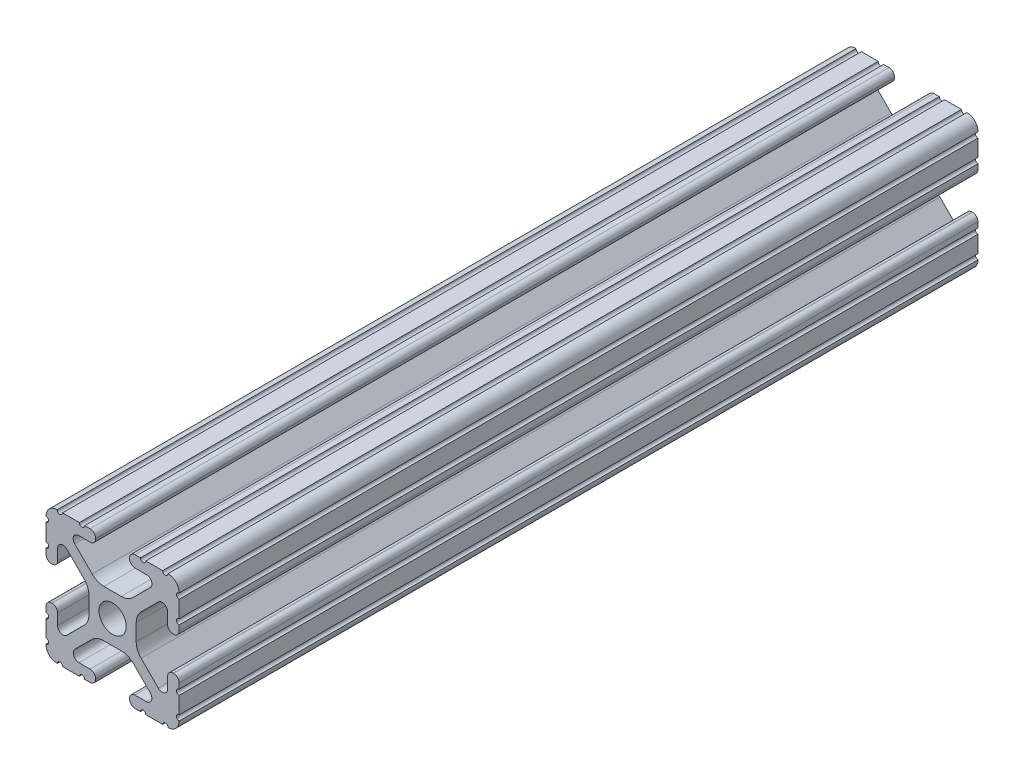
SolidWorks part; units mm, degrees
ref_plane "Front Plane" through (0, 0, 0) normal (0, 0, 1) x (1, 0, 0)
ref_plane "Top Plane" through (0, 0, 0) normal (0, 1, 0) x (1, 0, 0)
ref_plane "Right Plane" through (0, 0, 0) normal (1, 0, 0) x (0, 0, -1)
sketch "Sketch1" plane through (0, 0, 0) normal (0, 0, 1) x (1, 0, 0)
  line L0 (-7.207, 8.7244) -> (-3.8983, 5.4232)
  line L1 (-4.2875, 10.4902) -> (-6.4768, 10.4902)
  line L2 (-3.2385, 11.651) -> (-3.2385, 11.5392)
  line L3 (-5.3171, 12.7) -> (-4.2875, 12.7)
  line L4 (0, 13.4005) -> (0, -14.8534) construction
  line L5 (12.7, 0) -> (-13.9989, 0) construction
  line L6 (-9.5504, 12.7) -> (-6.3331, 12.7)
  line L7 (-12.7, 6.3331) -> (-12.7, 9.5504)
  line L8 (-12.7, 4.2875) -> (-12.7, 5.3171)
  line L9 (-11.5392, 3.2385) -> (-11.651, 3.2385)
  line L10 (-10.4902, 6.4021) -> (-10.4902, 4.2875)
  line L11 (-5.441, 3.8408) -> (-8.7371, 7.1294)
  line L12 (-4.5085, -1.5932) -> (-4.5085, 1.5932)
  line L13 (-1.7093, -4.4958) -> (1.7093, -4.4958)
  line L14 (3.9523, -5.4237) -> (7.1797, -8.6452)
  line L15 (6.4164, -10.4902) -> (4.2875, -10.4902)
  line L16 (3.2385, -11.5392) -> (3.2385, -11.651)
  line L17 (4.2875, -12.7) -> (5.3171, -12.7)
  line L18 (6.3331, -12.7) -> (9.5504, -12.7)
  line L19 (12.7, -9.5504) -> (12.7, -6.3331)
  line L20 (12.7, -5.3171) -> (12.7, -4.2875)
  line L21 (11.651, -3.2385) -> (11.5392, -3.2385)
  line L22 (10.4902, -4.2875) -> (10.4902, -6.4021)
  line L23 (8.7371, -7.1294) -> (5.441, -3.8408)
  line L24 (4.5085, -1.5932) -> (4.5085, 1.5932)
  line L25 (5.441, 3.8408) -> (8.7371, 7.1294)
  line L26 (10.4902, 6.4021) -> (10.4902, 4.2875)
  line L27 (11.5392, 3.2385) -> (11.651, 3.2385)
  line L28 (12.7, 4.2875) -> (12.7, 5.3171)
  line L29 (12.7, 6.3331) -> (12.7, 9.5504)
  line L30 (9.5504, 12.7) -> (6.3331, 12.7)
  line L31 (5.3171, 12.7) -> (4.2875, 12.7)
  line L32 (3.2385, 11.651) -> (3.2385, 11.5392)
  line L33 (4.2875, 10.4902) -> (6.4768, 10.4902)
  line L34 (7.207, 8.7244) -> (3.8983, 5.4232)
  line L35 (1.6558, 4.4958) -> (-1.6558, 4.4958)
  line L36 (-8.7371, -7.1294) -> (-5.441, -3.8408)
  line L37 (-10.4902, -4.2875) -> (-10.4902, -6.4021)
  line L38 (-11.651, -3.2385) -> (-11.5392, -3.2385)
  line L39 (-12.7, -5.3171) -> (-12.7, -4.2875)
  line L40 (-12.7, -9.5504) -> (-12.7, -6.3331)
  line L41 (-6.3331, -12.7) -> (-9.5504, -12.7)
  line L42 (-4.2875, -12.7) -> (-5.3171, -12.7)
  line L43 (-3.2385, -11.5392) -> (-3.2385, -11.651)
  line L44 (-6.4164, -10.4902) -> (-4.2875, -10.4902)
  line L45 (-3.9523, -5.4237) -> (-7.1797, -8.6452)
  arc A0 (-7.207, 8.7244) -> (-6.4768, 10.4902) centre (-6.4768, 9.4563) cw
  arc A1 (-3.2385, 11.5392) -> (-4.2875, 10.4902) centre (-4.2875, 11.5392) cw
  arc A2 (-4.2875, 12.7) -> (-3.2385, 11.651) centre (-4.2875, 11.651) cw
  arc A3 (-5.3171, 12.7) -> (-6.3331, 12.7) centre (-5.8251, 12.7) cw
  arc A4 (-9.5504, 12.7) -> (-10.5664, 12.6998) centre (-10.0584, 12.7) cw
  arc A5 (-12.6998, 10.5664) -> (-10.5664, 12.6998) centre (-10.5918, 10.5918) cw
  arc A6 (-12.6998, 10.5664) -> (-12.7, 9.5504) centre (-12.7, 10.0584) cw
  arc A7 (-12.7, 6.3331) -> (-12.7, 5.3171) centre (-12.7, 5.8251) cw
  arc A8 (-11.651, 3.2385) -> (-12.7, 4.2875) centre (-11.651, 4.2875) cw
  arc A9 (-10.4902, 4.2875) -> (-11.5392, 3.2385) centre (-11.5392, 4.2875) cw
  circle A10 centre (0, 0) radius 2.6035
  arc A11 (-10.4902, 6.4021) -> (-8.7371, 7.1294) centre (-9.4628, 6.4021) cw
  arc A12 (-5.441, 3.8408) -> (-4.5085, 1.5932) centre (-7.6835, 1.5932) cw
  arc A13 (-4.5085, -1.5932) -> (-5.441, -3.8408) centre (-7.6835, -1.5932) cw
  arc A14 (-8.7371, -7.1294) -> (-10.4902, -6.4021) centre (-9.4628, -6.4021) cw
  arc A15 (-1.7093, -4.4958) -> (-3.9523, -5.4237) centre (-1.7093, -7.6708) ccw
  arc A16 (3.9523, -5.4237) -> (1.7093, -4.4958) centre (1.7093, -7.6708) ccw
  arc A17 (6.4164, -10.4902) -> (7.1797, -8.6452) centre (6.4164, -9.4098) ccw
  arc A18 (4.2875, -10.4902) -> (3.2385, -11.5392) centre (4.2875, -11.5392) ccw
  arc A19 (3.2385, -11.651) -> (4.2875, -12.7) centre (4.2875, -11.651) ccw
  arc A20 (6.3331, -12.7) -> (5.3171, -12.7) centre (5.8251, -12.7) ccw
  arc A21 (10.5664, -12.6998) -> (9.5504, -12.7) centre (10.0584, -12.7) ccw
  arc A22 (10.5664, -12.6998) -> (12.6998, -10.5664) centre (10.5918, -10.5918) ccw
  arc A23 (12.7, -9.5504) -> (12.6998, -10.5664) centre (12.7, -10.0584) ccw
  arc A24 (12.7, -5.3171) -> (12.7, -6.3331) centre (12.7, -5.8251) ccw
  arc A25 (12.7, -4.2875) -> (11.651, -3.2385) centre (11.651, -4.2875) ccw
  arc A26 (11.5392, -3.2385) -> (10.4902, -4.2875) centre (11.5392, -4.2875) ccw
  arc A27 (8.7371, -7.1294) -> (10.4902, -6.4021) centre (9.4628, -6.4021) ccw
  arc A28 (4.5085, -1.5932) -> (5.441, -3.8408) centre (7.6835, -1.5932) ccw
  arc A29 (5.441, 3.8408) -> (4.5085, 1.5932) centre (7.6835, 1.5932) ccw
  arc A30 (10.4902, 6.4021) -> (8.7371, 7.1294) centre (9.4628, 6.4021) ccw
  arc A31 (10.4902, 4.2875) -> (11.5392, 3.2385) centre (11.5392, 4.2875) ccw
  arc A32 (11.651, 3.2385) -> (12.7, 4.2875) centre (11.651, 4.2875) ccw
  arc A33 (12.7, 6.3331) -> (12.7, 5.3171) centre (12.7, 5.8251) ccw
  arc A34 (12.6998, 10.5664) -> (12.7, 9.5504) centre (12.7, 10.0584) ccw
  arc A35 (12.6998, 10.5664) -> (10.5664, 12.6998) centre (10.5918, 10.5918) ccw
  arc A36 (9.5504, 12.7) -> (10.5664, 12.6998) centre (10.0584, 12.7) ccw
  arc A37 (5.3171, 12.7) -> (6.3331, 12.7) centre (5.8251, 12.7) ccw
  arc A38 (4.2875, 12.7) -> (3.2385, 11.651) centre (4.2875, 11.651) ccw
  arc A39 (3.2385, 11.5392) -> (4.2875, 10.4902) centre (4.2875, 11.5392) ccw
  arc A40 (7.207, 8.7244) -> (6.4768, 10.4902) centre (6.4768, 9.4563) ccw
  arc A41 (1.6558, 4.4958) -> (3.8983, 5.4232) centre (1.6558, 7.6708) ccw
  arc A42 (-1.6558, 4.4958) -> (-3.8983, 5.4232) centre (-1.6558, 7.6708) cw
  arc A43 (-11.5392, -3.2385) -> (-10.4902, -4.2875) centre (-11.5392, -4.2875) cw
  arc A44 (-12.7, -4.2875) -> (-11.651, -3.2385) centre (-11.651, -4.2875) cw
  arc A45 (-12.7, -5.3171) -> (-12.7, -6.3331) centre (-12.7, -5.8251) cw
  arc A46 (-12.7, -9.5504) -> (-12.6998, -10.5664) centre (-12.7, -10.0584) cw
  arc A47 (-10.5664, -12.6998) -> (-12.6998, -10.5664) centre (-10.5918, -10.5918) cw
  arc A48 (-10.5664, -12.6998) -> (-9.5504, -12.7) centre (-10.0584, -12.7) cw
  arc A49 (-6.3331, -12.7) -> (-5.3171, -12.7) centre (-5.8251, -12.7) cw
  arc A50 (-3.2385, -11.651) -> (-4.2875, -12.7) centre (-4.2875, -11.651) cw
  arc A51 (-4.2875, -10.4902) -> (-3.2385, -11.5392) centre (-4.2875, -11.5392) cw
  arc A52 (-6.4164, -10.4902) -> (-7.1797, -8.6452) centre (-6.4164, -9.4098) cw
  dimension "D1" = 5.207
  dimension "D9" = 14.859
  dimension "D2" = 25.4
  dimension "D3" = 12.7
  dimension "D4" = 6.477
  dimension "D5" = 8.2042
  dimension "D6" = 9.017
  dimension "D8" = 2.2098
  dimension "D10" = 2.2098
extrude "Extrude1" add sketch "Sketch1" against normal blind 152.4
